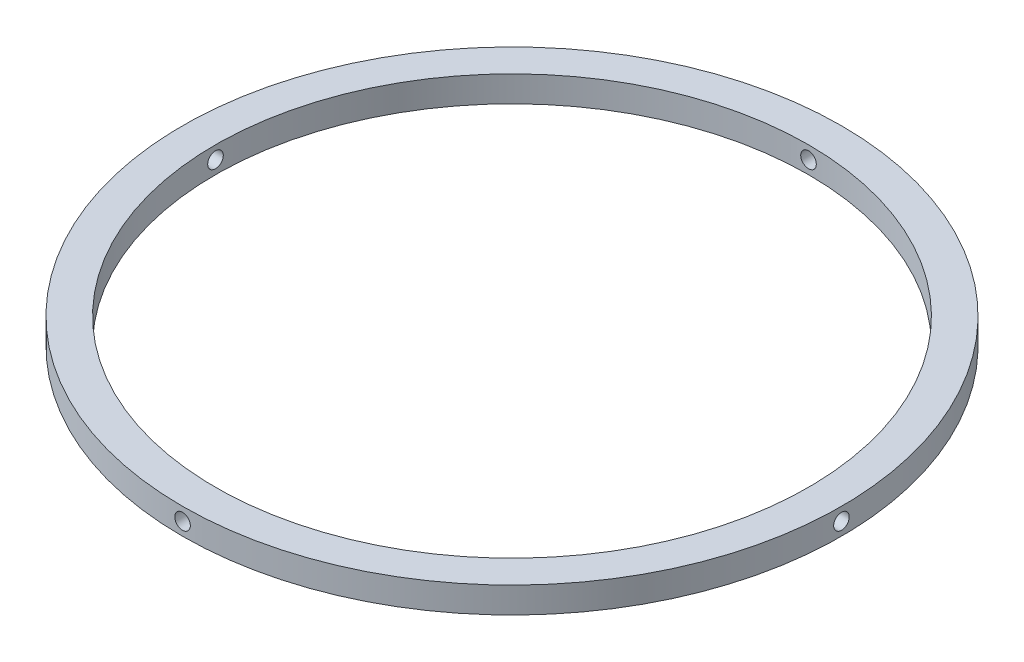
SolidWorks part; units mm, degrees
ref_plane "Front Plane" through (0, 0, 0) normal (0, 0, 1) x (1, 0, 0)
ref_plane "Top Plane" through (0, 0, 0) normal (0, 1, 0) x (1, 0, 0)
ref_plane "Right Plane" through (0, 0, 0) normal (1, 0, 0) x (0, 0, -1)
sketch "Outer Ring Main Sketch" plane through (0, 0, 0) normal (0, 1, 0) x (1, 0, 0)
  circle A0 centre (0, 0) radius 63.5
  dimension "D1" = 127
extrude "Outer Ring Main Body" add sketch "Outer Ring Main Sketch" along normal blind 5
sketch "Center Hole Sketch" plane through (0, 0, 0) normal (0, -1, 0) x (1, 0, 0)
  circle A0 centre (0, 0) radius 57.15
  dimension "D1" = 114.3
extrude "Center Hole" cut sketch "Center Hole Sketch" against normal through all
sketch "Pin Hole Sketch" plane through (0, 0, 0) normal (0, 0, 1) x (1, 0, 0)
  line L0 (-63.5, 5) -> (-63.5, 0) construction
  line L1 (63.5, 5) -> (-63.5, 5) construction
  line L2 (63.5, 0) -> (63.5, 5) construction
  line L3 (-63.5, 0) -> (63.5, 0) construction
  line L4 (-63.5, 5) -> (-63.5, 0) construction
  line L5 (63.5, 5) -> (-63.5, 5) construction
  line L6 (63.5, 0) -> (63.5, 5) construction
  line L7 (-63.5, 0) -> (63.5, 0) construction
  line L8 (0, 38.9259) -> (0, -26.8884) construction
  line L9 (78.5361, 2.5) -> (-89.9551, 2.5) construction
  circle A0 centre (0, 2.5) radius 1.5
  point P10 (0, 2.5)
  point P12 (-3.1305, 2.5)
  point P13 (-3.6919, 2.5)
  dimension "D6" = 3
  dimension "D1" = 63.5
  dimension "D2" = 127
  dimension "D3" = 5
  dimension "D4" = 2.5
  dimension "D5" = 0
extrude "Pin Hole" cut sketch "Pin Hole Sketch" against normal through all both and the other way through all
sketch "Pin Hole 2 Sketch" plane through (0, 0, 0) normal (1, 0, 0) x (0, 0, -1)
  line L0 (-63.5, 0) -> (63.5, 0) construction
  line L1 (63.5, 5) -> (-63.5, 5) construction
  line L2 (-63.5, 0) -> (63.5, 0) construction
  line L3 (63.5, 5) -> (-63.5, 5) construction
  line L4 (0, 32.931) -> (0, -21.2844) construction
  line L5 (69.0724, 2.5) -> (-67.7692, 2.5) construction
  circle A0 centre (0, 2.5) radius 1.5
  spline S0 degree 2 poles (63.5, 1) (63.4646, 2.5) (63.5, 4) knots 0 0 0 1 1 1 weights 0.062 0.0635 0.065 construction
  spline S1 degree 2 poles (-63.5, 4) (-63.4646, 2.5) (-63.5, 1) knots 0 0 0 1 1 1 weights 0.062 0.0635 0.065 construction
  spline S2 degree 2 poles (63.5, 1) (63.4646, 2.5) (63.5, 4) knots 0 0 0 1 1 1 weights 0.062 0.0635 0.065 construction
  spline S3 degree 2 poles (-63.5, 4) (-63.4646, 2.5) (-63.5, 1) knots 0 0 0 1 1 1 weights 0.062 0.0635 0.065 construction
  dimension "D6" = 3
  dimension "D2" = 127
  dimension "D5" = 0
  dimension "D1" = 5
  dimension "D3" = 2.5
  dimension "D4" = 63.5
extrude "Pin Hole 2" cut sketch "Pin Hole 2 Sketch" against normal through all both and the other way through all
equation "\"D1@Pin Hole Sketch\" = \"D2@Pin Hole Sketch\" * 0.5"
equation "\"D4@Pin Hole Sketch\" = \"D3@Pin Hole Sketch\" * 0.5"
equation "\"D3@Pin Hole 2 Sketch\"=\"D1@Pin Hole 2 Sketch\"*0.5"
equation "\"D4@Pin Hole 2 Sketch\"=\"D2@Pin Hole 2 Sketch\"*0.5"
equation "\"D5@Pin Hole 2 Sketch\"=0"
